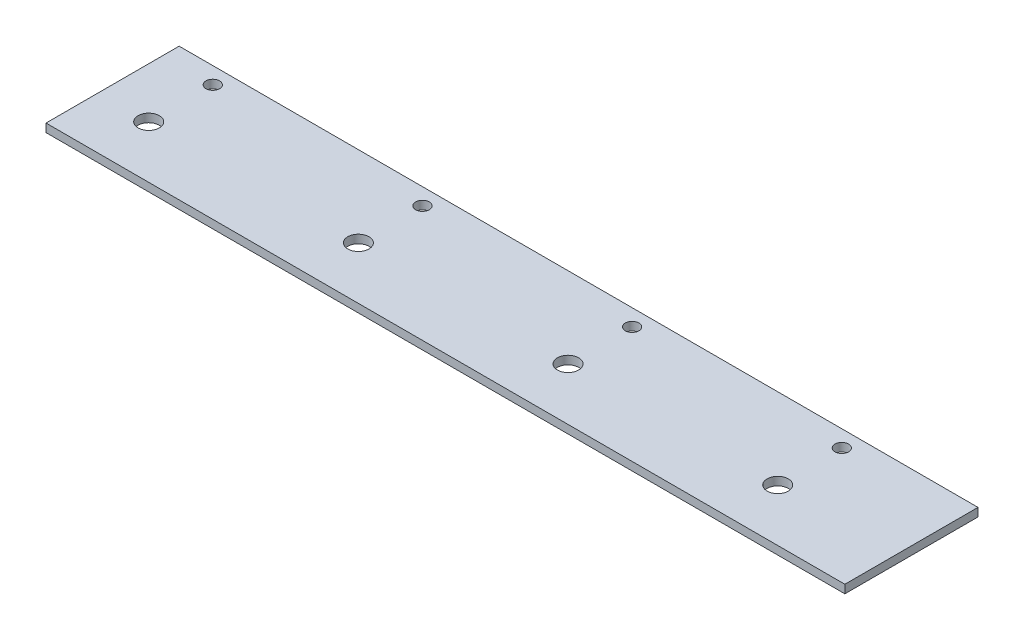
SolidWorks part; units mm, degrees
ref_plane "Front Plane" through (0, 0, 0) normal (0, 0, 1) x (1, 0, 0)
ref_plane "Top Plane" through (0, 0, 0) normal (0, 1, 0) x (1, 0, 0)
ref_plane "Right Plane" through (0, 0, 0) normal (1, 0, 0) x (0, 0, -1)
sketch "Sketch1" plane through (0, 0, 0) normal (0, 1, 0) x (1, 0, 0)
  line L0 (0, 44.45) -> (304.8, 44.45) construction
  line L1 (0, 0) -> (304.8, 0)
  line L2 (0, 0) -> (0, 50.8)
  line L3 (0, 50.8) -> (304.8, 50.8)
  line L4 (304.8, 0) -> (304.8, 50.8)
  line L5 (19.1851, 44.45) -> (19.1851, 20) construction
  line L6 (0, 20) -> (304.8, 20) construction
  circle A0 centre (19.1851, 44.45) radius 2.6
  circle A1 centre (19.1851, 20) radius 4.05
  circle A2 centre (99.1851, 20) radius 4.05
  circle A3 centre (99.1851, 44.45) radius 2.6
  circle A4 centre (179.1851, 20) radius 4.05
  circle A5 centre (179.1851, 44.45) radius 2.6
  circle A6 centre (259.1851, 20) radius 4.05
  circle A7 centre (259.1851, 44.45) radius 2.6
  dimension "D5" = 5.2
  dimension "D6" = 8.1
  dimension "D1" = 50.8
  dimension "D2" = 304.8
  dimension "D3" = 20
  dimension "D4" = 6.35
  dimension "D7" = 19.1851
  dimension "D9" = 80
  dimension "D8" = 4
extrude "Boss-Extrude1" add sketch "Sketch1" along normal blind 3.175
